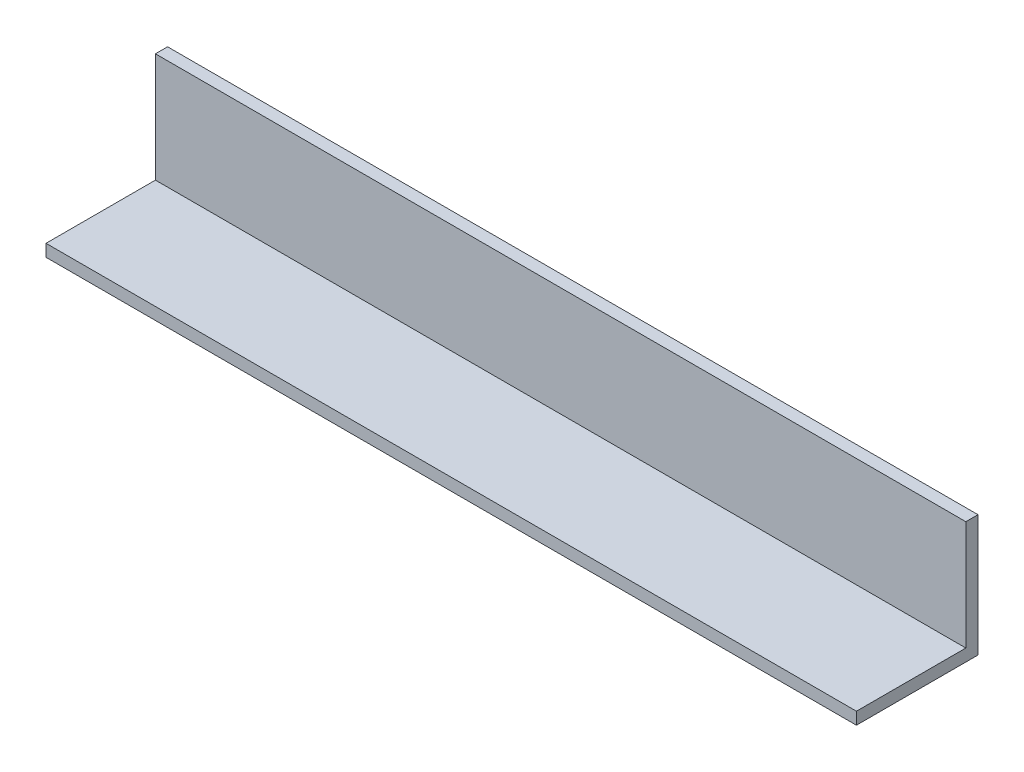
SolidWorks part; units mm, degrees
ref_plane "Alzado" through (0, 0, 0) normal (0, 0, 1) x (1, 0, 0)
ref_plane "Planta" through (0, 0, 0) normal (0, 1, 0) x (1, 0, 0)
ref_plane "Vista lateral" through (0, 0, 0) normal (1, 0, 0) x (0, 0, -1)
sketch "Croquis1" plane through (0, 0, 0) normal (1, 0, 0) x (0, 0, -1)
  line L1 (0, 0) -> (-15, 0)
  line L3 (-1.5, 1.5) -> (-15, 1.5)
  line L4 (-15, 0) -> (-15, 1.5)
  line L6 (0, 0) -> (0, 15)
  line L7 (0, 15) -> (-1.5, 15)
  line L8 (-1.5, 1.5) -> (-1.5, 15)
  dimension "D1" = 15
  dimension "D2" = 1.5
  dimension "D3" = 15
  dimension "D4" = 1.5
extrude "Saliente-Extruir1" add sketch "Croquis1" along normal blind 100
